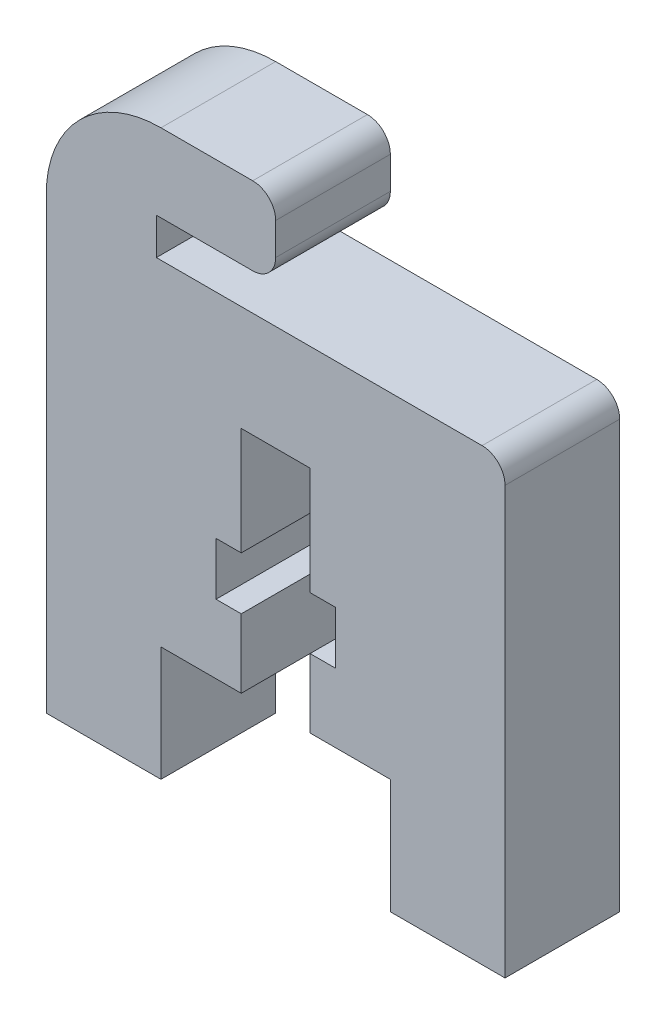
SolidWorks part; units mm, degrees
ref_plane "Front Plane" through (0, 0, 0) normal (0, 0, 1) x (1, 0, 0)
ref_plane "Top Plane" through (0, 0, 0) normal (0, 1, 0) x (1, 0, 0)
ref_plane "Right Plane" through (0, 0, 0) normal (1, 0, 0) x (0, 0, -1)
sketch "Sketch1" plane through (0, 0, 0) normal (0, 0, 1) x (1, 0, 0)
  line L0 (0, 5) -> (0, 19.9828)
  line L1 (20, 5) -> (20, 19.6)
  line L2 (20, 19.6) -> (4.8, 19.6)
  line L3 (4.8, 19.6) -> (4.8, 21.2)
  line L4 (4.8, 21.2) -> (10, 21.2)
  line L5 (10, 21.2) -> (10, 24.6)
  line L6 (10, 24.6) -> (0, 24.6)
  line L7 (0, 24.6) -> (0, 19.9828)
  line L8 (10, 5) -> (10, 16.2208) construction
  line L9 (8.5, 5) -> (5, 5)
  line L10 (5, 0) -> (0, 0)
  line L11 (0, 0) -> (0, 5)
  line L12 (5, 0) -> (5, 5)
  line L13 (11.5, 5) -> (15, 5)
  line L14 (15, 5) -> (15, 0)
  line L15 (15, 0) -> (20, 0)
  line L16 (20, 0) -> (20, 5)
  line L17 (8.5, 5) -> (11.5, 5) construction
  line L18 (11.5, 5) -> (11.5, 8)
  line L19 (11.5, 10.3) -> (12.6, 10.3)
  line L20 (7.4, 8) -> (7.4, 10.3)
  line L21 (12.6, 8) -> (11.5, 8)
  line L22 (11.5, 10.3) -> (11.5, 15)
  line L23 (11.5, 15) -> (8.5, 15)
  line L24 (8.5, 15) -> (8.5, 10.3)
  line L25 (8.5, 8) -> (7.4, 8)
  line L26 (12.6, 10.3) -> (12.6, 8)
  line L27 (7.4, 10.3) -> (8.5, 10.3)
  line L28 (8.5, 8) -> (8.5, 5)
  line L29 (10, 15) -> (10, 5) construction
  dimension "D1" = 1.6
  dimension "D2" = 14.6
  dimension "D3" = 4.8
  dimension "D4" = 3.4
  dimension "D5" = 10
  dimension "D6" = 5
  dimension "D7" = 5
  dimension "D8" = 5.2
  dimension "D9" = 3
  dimension "D10" = 2.3
  dimension "D11" = 3
  dimension "D12" = 10
  dimension "D13" = 10
extrude "Boss-Extrude1" add sketch "Sketch1" along normal blind 5
fillet "Fillet1" radius 5 1 edges at (0, 24.6, 2.5)
fillet "Fillet3" radius 1 2 edges at (20, 19.6, 2.5) (10, 21.2, 2.5)
fillet "Fillet4" radius 1 1 edges at (10, 24.6, 2.5)
